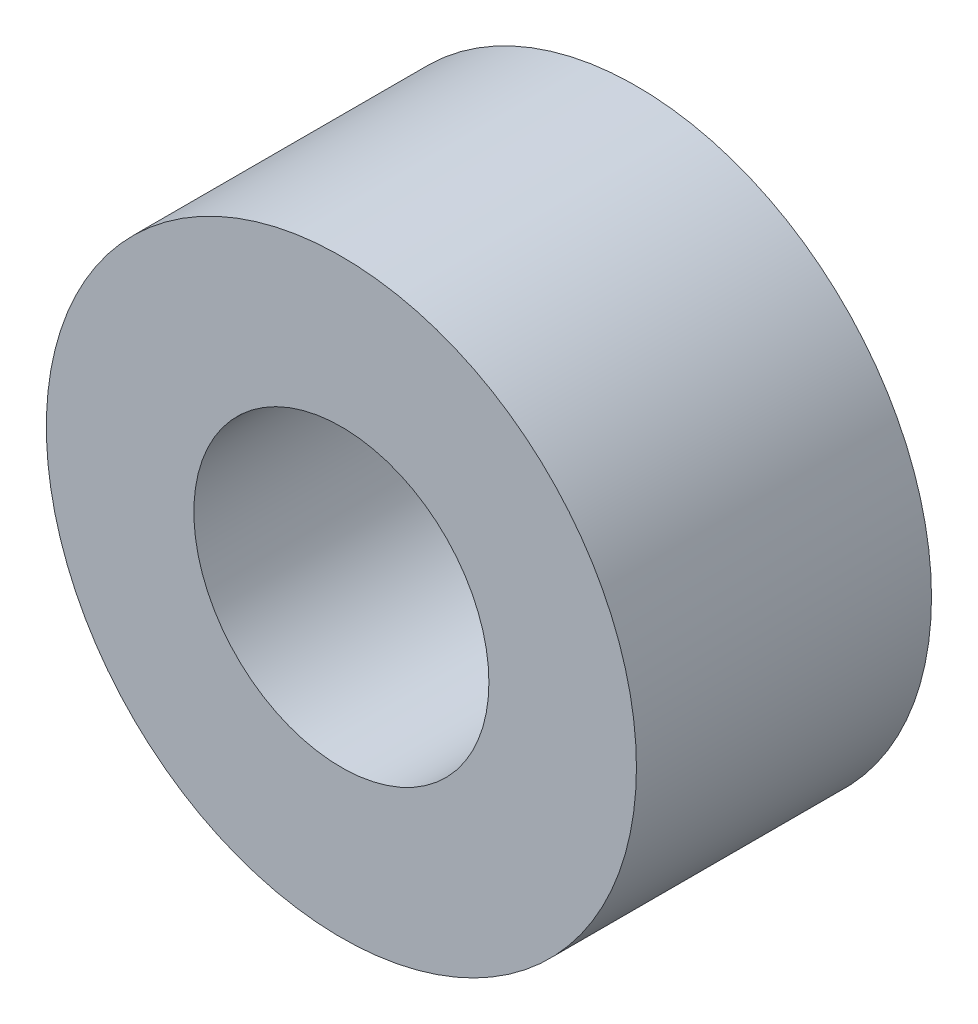
SolidWorks part; units mm, degrees
material "普通碳钢"
ref_plane "前视" through (0, 0, 0) normal (0, 0, 1) x (1, 0, 0)
ref_plane "上视" through (0, 0, 0) normal (0, 1, 0) x (1, 0, 0)
ref_plane "右视" through (0, 0, 0) normal (1, 0, 0) x (0, 0, -1)
sketch "草图1" plane through (0, 0, 0) normal (0, 0, 1) x (1, 0, 0)
  circle A0 centre (0, 0) radius 3
  circle A1 centre (0, 0) radius 1.5
  dimension "D1" = 6
  dimension "D2" = 3
extrude "凸台-拉伸1" add sketch "草图1" along normal blind 3
